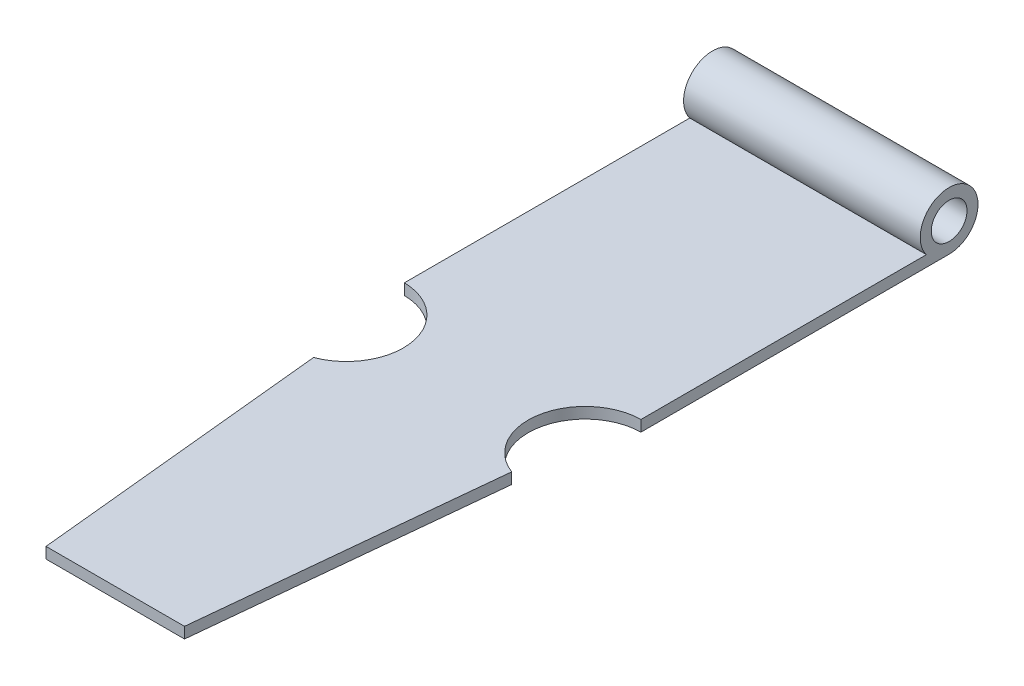
SolidWorks part; units mm, degrees
ref_plane "Спереди" through (0, 0, 0) normal (0, 0, 1) x (1, 0, 0)
ref_plane "Сверху" through (0, 0, 0) normal (0, 1, 0) x (1, 0, 0)
ref_plane "Справа" through (0, 0, 0) normal (1, 0, 0) x (0, 0, -1)
other "Configuration Table"
sketch "Эскиз1" plane through (0, 0, 0) normal (0, 1, 0) x (1, 0, 0)
  line L0 (-21.495, 0) -> (21.495, 0)
  line L3 (-12.58, -130) -> (12.58, -130)
  line L4 (0, 0) -> (0, -130) construction
  line L5 (-19.0974, -65) -> (19.0974, -65) construction
  line L6 (-21.495, 0) -> (-21.495, -55.9747)
  line L7 (-17.9947, -75.9747) -> (-12.58, -130)
  line L8 (17.9947, -75.9747) -> (12.58, -130)
  line L9 (21.495, 0) -> (21.495, -55.9747)
  arc A4 (-21.495, -55.9747) -> (-17.9947, -75.9747) centre (-21.6806, -66.3135) cw
  arc A5 (21.495, -55.9747) -> (17.9947, -75.9747) centre (21.6806, -66.3135) ccw
  point P0 (0, -130)
  point P4 (0, 0)
  point P15 (-11.495, -64.5308)
  dimension "D5" = 20
  dimension "D6" = 10
  dimension "D7" = 17.9947
  dimension "D1" = 25.16
  dimension "D2" = 42.99
  dimension "D3" = 130
  dimension "D4" = 65
  dimension "D8" = 55.9747
extrude "Бобышка-Вытянуть1" add sketch "Эскиз1" along normal blind 2
sketch "Эскиз4" plane through (21.495, 0, 0.5694) normal (1, 0, 0) x (0, 0, -1)
  line L4 (0.5694, 0) -> (0.5694, 5.25) construction
  line L5 (0.5694, 0) -> (-55.4053, 0) construction
  circle A0 centre (0.5694, 5.25) radius 5.25
  circle A1 centre (0.5694, 5.25) radius 3.25
  dimension "D1" = 2
  dimension "D2" = 10.5
extrude "Бобышка-Вытянуть4" add sketch "Эскиз4" against normal up to surface (42.99 mm away) up to face at (-21.495, 1, 27.9873)
